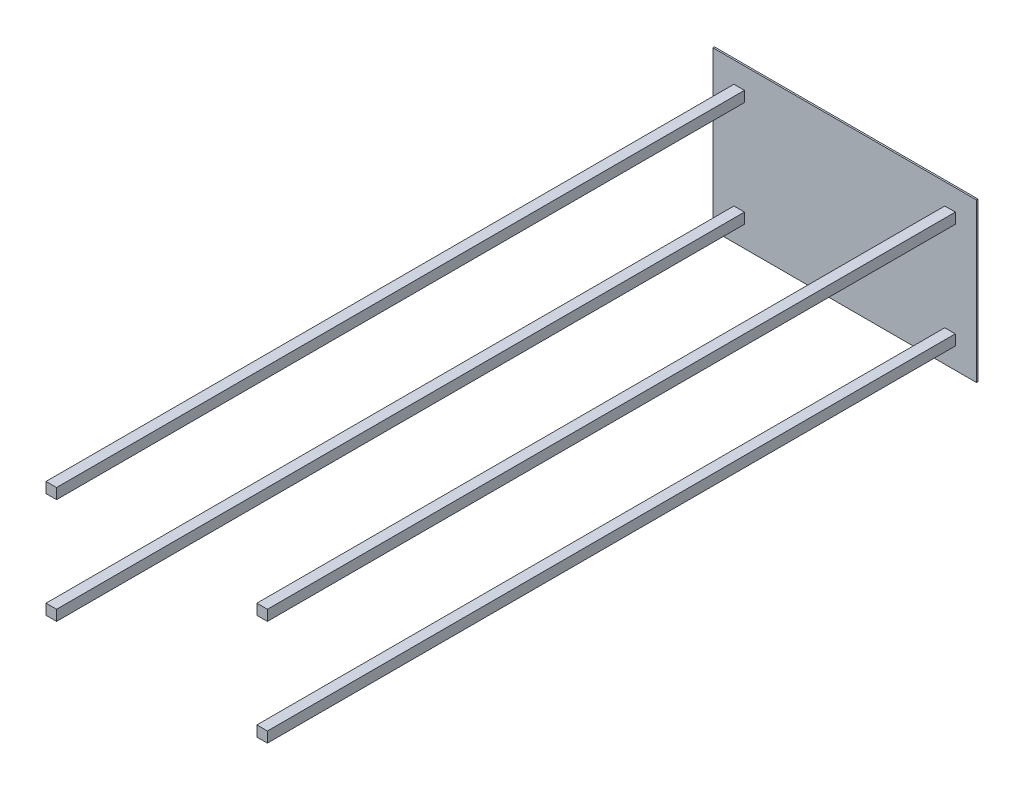
SolidWorks part; units mm, degrees
ref_plane "Piano frontale" through (0, 0, 0) normal (0, 0, 1) x (1, 0, 0)
ref_plane "Piano superiore" through (0, 0, 0) normal (0, 1, 0) x (1, 0, 0)
ref_plane "Piano destro" through (0, 0, 0) normal (1, 0, 0) x (0, 0, -1)
sketch "Schizzo1" plane through (0, 0, 0) normal (0, 0, 1) x (1, 0, 0)
  line L1 (-250, -150) -> (250, -150)
  line L2 (-250, -150) -> (-250, 150)
  line L3 (-250, 150) -> (250, 150)
  line L4 (250, -150) -> (250, 150)
  line L5 (-250, -150) -> (250, 150) construction
  line L6 (-250, 150) -> (250, -150) construction
  point P0 (0, 0)
  dimension "D1" = 500
  dimension "D2" = 300
extrude "Estrusione-Estrusione1" add sketch "Schizzo1" along normal blind 3
sketch "Schizzo2" plane through (0, 0, 3) normal (0, 0, 1) x (1, 0, 0)
  line L1 (200, -100) -> (-200, -100) construction
  line L2 (200, -100) -> (200, 100) construction
  line L3 (200, 100) -> (-200, 100) construction
  line L4 (-200, -100) -> (-200, 100) construction
  line L5 (200, -100) -> (-200, 100) construction
  line L6 (200, 100) -> (-200, -100) construction
  line L7 (-210, 90) -> (-190, 90)
  line L8 (-210, 90) -> (-210, 110)
  line L9 (-210, 110) -> (-190, 110)
  line L10 (-190, 90) -> (-190, 110)
  line L11 (-210, 90) -> (-190, 110) construction
  line L12 (-210, 110) -> (-190, 90) construction
  point P0 (0, 0)
  dimension "D1" = 400
  dimension "D2" = 200
  dimension "D3" = 20
  dimension "D4" = 20
extrude "Estrusione-Estrusione2" add sketch "Schizzo2" along normal blind 1305
pattern_linear "Ripetizione a L1" count 2 spacing 400 along (1, 0, 0) of "Estrusione-Estrusione2"
pattern_linear "Ripetizione a L2" count 2 spacing 200 along (0, -1, 0) of "Ripetizione a L1", "Estrusione-Estrusione2"
